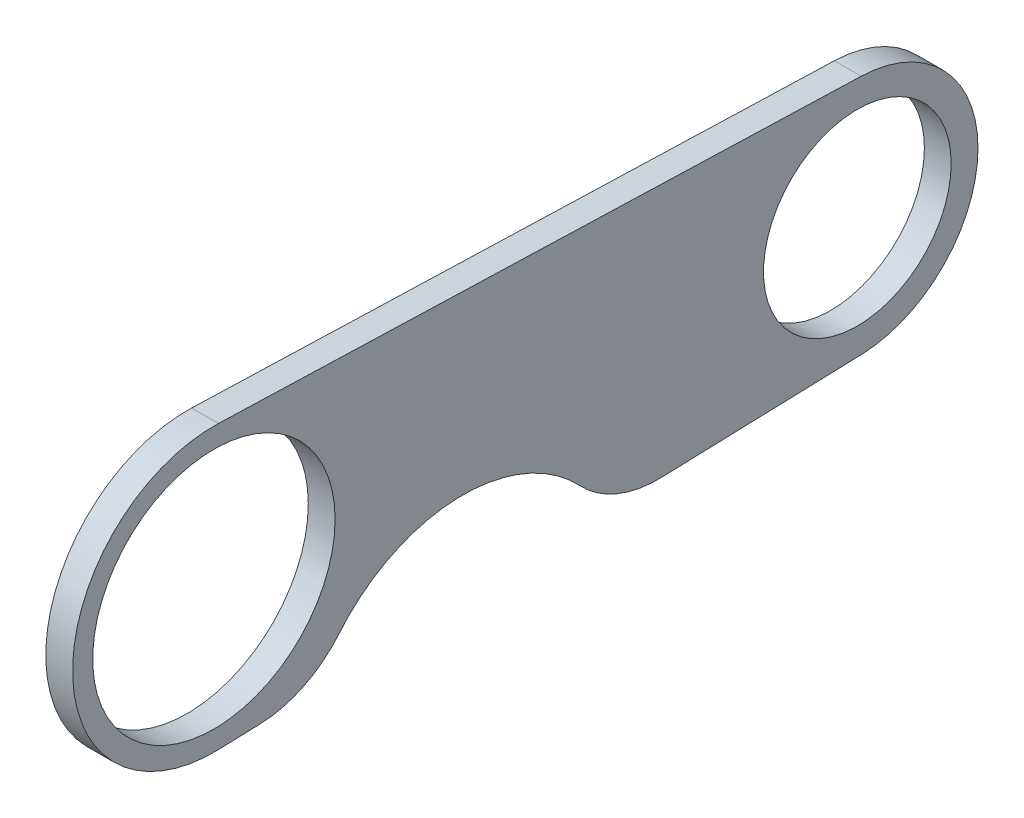
SolidWorks part; units mm, degrees
material "6061-T6 (SS)"
ref_plane "Front" through (0, 0, 0) normal (0, 0, 1) x (1, 0, 0)
ref_plane "Top" through (0, 0, 0) normal (0, 1, 0) x (1, 0, 0)
ref_plane "Right" through (0, 0, 0) normal (1, 0, 0) x (0, 0, -1)
sketch "Sketch1" plane through (0, 0, 0) normal (1, 0, 0) x (0, 0, -1)
  line L0 (-37.5632, 16.7236) -> (38.5584, 14.2801)
  line L3 (-37.5632, -16.7236) -> (38.5584, -14.2801)
  line L4 (-38.1, 0) -> (38.1, 0) construction
  circle A2 centre (-38.1, 0) radius 14.351
  circle A3 centre (38.1, 0) radius 11.1125
  arc A4 (38.5584, -14.2801) -> (38.5584, 14.2801) centre (38.1, 0) ccw
  arc A5 (-37.5632, 16.7236) -> (-37.5632, -16.7236) centre (-38.1, 0) ccw
  point P13 (0, 0)
  dimension "D1" = 28.702
  dimension "D2" = 2.3812
  dimension "D4" = 22.225
  dimension "D3" = 3.175
  dimension "D5" = 76.2
extrude "Boss-Extrude1" add sketch "Sketch1" along normal blind 3.175
sketch "Sketch2" plane through (3.175, 0, 0) normal (1, 0, 0) x (0, 0, -1)
  circle A0 centre (-8.6152, -24.13) radius 19.05
  circle A1 centre (-38.1, 0) radius 14.351 construction
  point P2 (-7.5596, -29.0939)
  dimension "D1" = 38.1
  dimension "D2" = 38.1
  dimension "D3" = 24.13
extrude "Cut-Extrude1" cut sketch "Sketch2" against normal through all
fillet "Fillet1" radius 12.7 2 edges at (1.5875, -15.2534, -8.2403) (1.5875, -16.3526, 26.0053)
